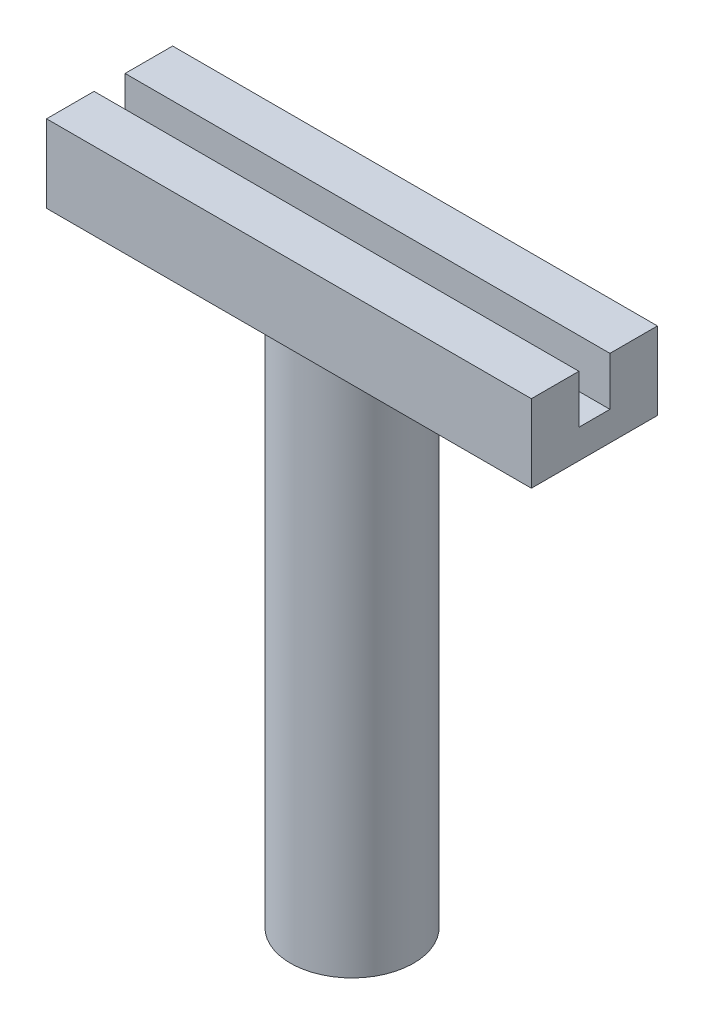
SolidWorks part; units mm, degrees
ref_plane "前视基准面" through (0, 0, 0) normal (0, 0, 1) x (1, 0, 0)
ref_plane "上视基准面" through (0, 0, 0) normal (0, 1, 0) x (1, 0, 0)
ref_plane "右视基准面" through (0, 0, 0) normal (1, 0, 0) x (0, 0, -1)
other "Configuration Table"
sketch "草图1" plane through (0, 0, 0) normal (0, 1, 0) x (1, 0, 0)
  line L1 (-25, -6.5) -> (25, -6.5)
  line L2 (-25, -6.5) -> (-25, 6.5)
  line L3 (-25, 6.5) -> (25, 6.5)
  line L4 (25, -6.5) -> (25, 6.5)
  line L5 (-25, -6.5) -> (25, 6.5) construction
  line L6 (-25, 6.5) -> (25, -6.5) construction
  point P0 (0, 0)
  dimension "D1" = 50
  dimension "D2" = 13
extrude "凸台-拉伸1" add sketch "草图1" along normal blind 8
sketch "草图2" plane through (0, 0, 0) normal (0, -1, 0) x (1, 0, 0)
  circle A0 centre (0, 0) radius 6.35
  dimension "D1" = 12.7
extrude "凸台-拉伸2" add sketch "草图2" along normal blind 55
sketch "草图3" plane through (0, 8, 0) normal (0, 1, 0) x (1, 0, 0)
  line L0 (25, -6.5) -> (25, 6.5) construction
  line L1 (-25, -1.6) -> (25, -1.6)
  line L2 (-25, -1.6) -> (-25, 1.6)
  line L3 (-25, 1.6) -> (25, 1.6)
  line L4 (25, -1.6) -> (25, 1.6)
  line L5 (-25, -1.6) -> (25, 1.6) construction
  line L6 (-25, 1.6) -> (25, -1.6) construction
  point P0 (0, 0)
  dimension "D1" = 3.2
extrude "切除-拉伸1" cut sketch "草图3" against normal blind 5
